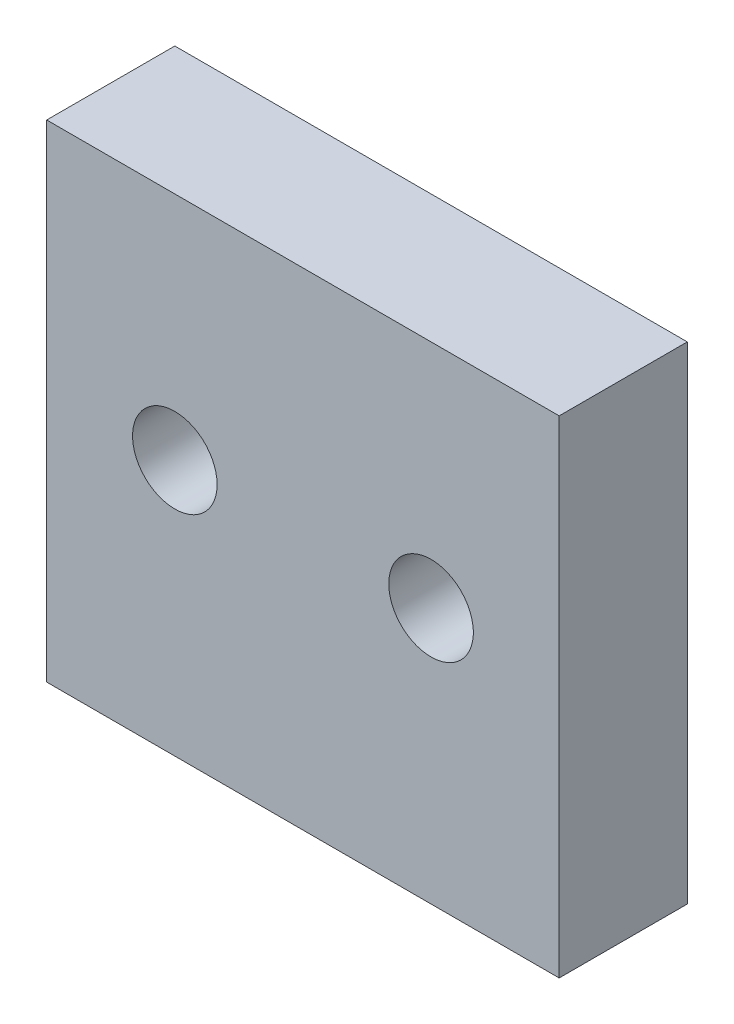
SolidWorks part; units mm, degrees
ref_plane "前视基准面" through (0, 0, 0) normal (0, 0, 1) x (1, 0, 0)
ref_plane "上视基准面" through (0, 0, 0) normal (0, 1, 0) x (1, 0, 0)
ref_plane "右视基准面" through (0, 0, 0) normal (1, 0, 0) x (0, 0, -1)
other "Configuration Table"
sketch "草图1" plane through (0, 0, 0) normal (0, 0, 1) x (1, 0, 0)
  line L0 (0, 0) -> (0, 13.4856) construction
  line L1 (-10, 10) -> (10, 10)
  line L2 (-10, 10) -> (-10, -10)
  line L3 (-10, -10) -> (10, -10)
  line L4 (10, 10) -> (10, -10)
  line L5 (-10, 10) -> (10, -10) construction
  line L6 (-10, -10) -> (10, 10) construction
  circle A0 centre (-5, 0) radius 1.65
  circle A1 centre (5, 0) radius 1.65
  point P0 (0, 0)
  dimension "D3" = 3.3
  dimension "D4" = 10
  dimension "D1" = 20
  dimension "D2" = 20
extrude "凸台-拉伸1" add sketch "草图1" along normal blind 5
sketch "草图2" plane through (0, 0, 5) normal (0, 0, 1) x (1, 0, 0)
  line L0 (10, -10) -> (10, 10) construction
  line L1 (-10, 10) -> (10, 10)
  line L2 (-10, 10) -> (-10, 9)
  line L3 (-10, 9) -> (10, 9)
  line L4 (10, 10) -> (10, 9)
  dimension "D1" = 1
extrude "切除-拉伸1" cut sketch "草图2" against normal blind 5
